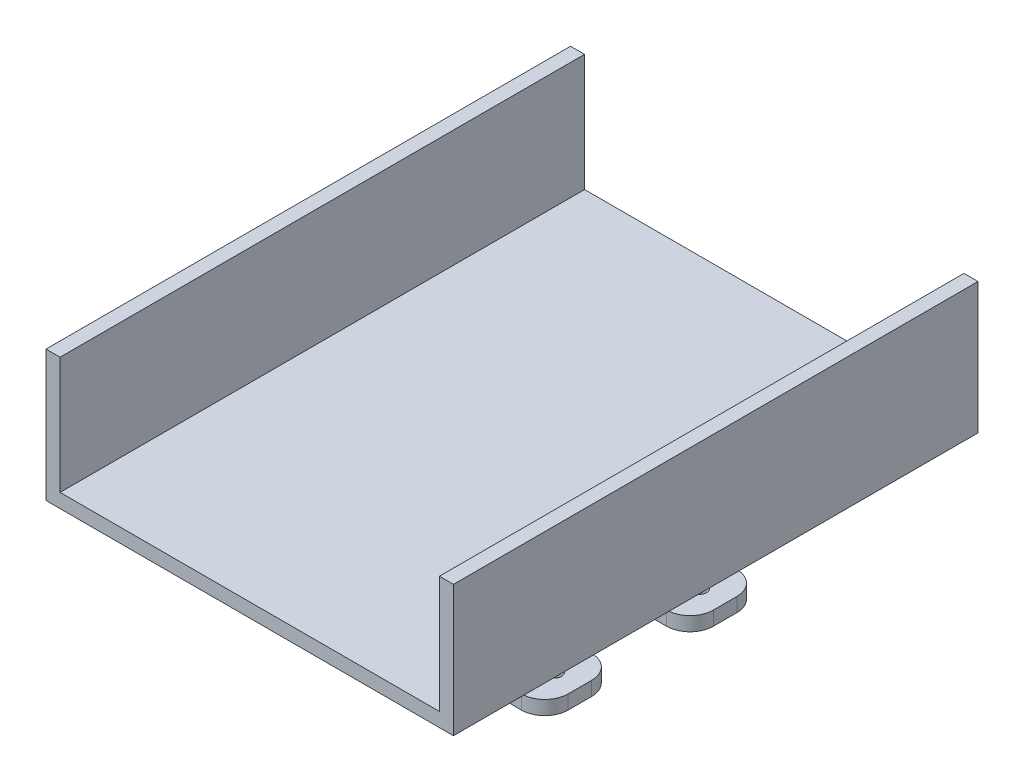
SolidWorks part; units mm, degrees
material "Du"
ref_plane "Front Plane" through (0, 0, 0) normal (0, 0, 1) x (1, 0, 0)
ref_plane "Top Plane" through (0, 0, 0) normal (0, 1, 0) x (1, 0, 0)
ref_plane "Right Plane" through (0, 0, 0) normal (1, 0, 0) x (0, 0, -1)
sketch "Sketch1" plane through (0, 0, 0) normal (0, 1, 0) x (1, 0, 0)
  line L1 (-43.5, -56) -> (43.5, -56)
  line L2 (-43.5, -56) -> (-43.5, 56)
  line L3 (-43.5, 56) -> (43.5, 56)
  line L4 (43.5, -56) -> (43.5, 56)
  line L5 (-43.5, -56) -> (43.5, 56) construction
  line L6 (-43.5, 56) -> (43.5, -56) construction
  point P0 (0, 0)
  dimension "D1" = 112
  dimension "D2" = 87
extrude "Boss-Extrude1" add sketch "Sketch1" along normal blind 3
sketch "Sketch2" plane through (0, 0, 0) normal (0, -1, 0) x (1, 0, 0)
  line L0 (0, 56) -> (0, -56) construction
  line L1 (-43.5, 56) -> (43.5, 56) construction
  line L2 (43.5, -56) -> (-43.5, -56) construction
  line L3 (-43.5, 0) -> (43.5, 0) construction
  line L4 (-43.5, -56) -> (-43.5, 56) construction
  line L5 (43.5, 56) -> (43.5, -56) construction
  line L6 (19, -14) -> (19, -17)
  line L7 (19, 14) -> (-19, 14)
  line L8 (19, 14) -> (19, 17)
  line L9 (19, 17) -> (-19, 17)
  line L10 (-19, 14) -> (-19, 17)
  line L11 (19, 14) -> (-19, 17) construction
  line L12 (19, 17) -> (-19, 14) construction
  line L13 (19, -14) -> (-19, -17) construction
  line L14 (19, -17) -> (-19, -14) construction
  line L15 (19, -14) -> (-19, -14)
  line L16 (-19, -14) -> (-19, -17)
  line L17 (19, -17) -> (-19, -17)
  point P12 (0, 15.5)
  point P21 (0, -15.5)
  dimension "D1" = 3
  dimension "D2" = 38
  dimension "D3" = 31
extrude "Boss-Extrude2" add sketch "Sketch2" along normal blind 18
sketch "Sketch8" plane through (0, -18, 0) normal (0, -1, 0) x (1, 0, 0)
  line L0 (19, -14) -> (-19, -14) construction
  line L1 (-19, -14) -> (-19, -17) construction
  line L2 (-19, -17) -> (19, -17) construction
  line L3 (19, -17) -> (19, -14) construction
  line L4 (-19, 17) -> (-19, 14) construction
  line L5 (-19, 14) -> (19, 14) construction
  line L6 (19, 14) -> (19, 17) construction
  line L7 (19, 17) -> (-19, 17) construction
  line L8 (19, -14) -> (-19, -14)
  line L9 (-19, -14) -> (-19, -17)
  line L10 (-19, -17) -> (19, -17)
  line L11 (19, -17) -> (19, -14)
  line L12 (-19, 17) -> (-19, 14)
  line L13 (-19, 14) -> (19, 14)
  line L14 (19, 14) -> (19, 17)
  line L15 (19, 17) -> (-19, 17)
  line L16 (0, 17) -> (0, -17) construction
  line L17 (-19, 15.5) -> (19, 15.5) construction
  line L18 (-19, -15.5) -> (19, -15.5) construction
  line L20 (30, 8) -> (-30, 8)
  line L21 (30, 8) -> (30, 23)
  line L22 (30, 23) -> (-30, 23)
  line L23 (-30, 8) -> (-30, 23)
  line L24 (30, 8) -> (-30, 23) construction
  line L25 (30, 23) -> (-30, 8) construction
  line L26 (30, -23) -> (-30, -23)
  line L27 (30, -23) -> (30, -8)
  line L28 (30, -8) -> (-30, -8)
  line L29 (-30, -23) -> (-30, -8)
  line L30 (30, -23) -> (-30, -8) construction
  line L31 (30, -8) -> (-30, -23) construction
  circle A0 centre (-24.5, 15.5) radius 1.575
  circle A1 centre (24.5, 15.5) radius 1.575
  circle A2 centre (-24.5, -15.5) radius 1.575
  circle A3 centre (24.5, -15.5) radius 1.575
  point P14 (0, 15.5)
  point P19 (0, -15.5)
  dimension "D5" = 3.15
  dimension "D7" = 3.15
  dimension "D1" = 15
  dimension "D2" = 60
  dimension "D3" = 15
  dimension "D4" = 60
  dimension "D6" = 5.5
  dimension "D8" = 5.5
extrude "Boss-Extrude5" add sketch "Sketch8" along normal blind 3 separate body
sketch "Sketch9" plane through (0, 0, 14) normal (0, 0, 1) x (1, 0, 0)
  line L4 (19, -18) -> (-19, -18)
  line L5 (-19, -18) -> (-19, -21)
  line L6 (-19, -21) -> (19, -21)
  line L7 (19, -21) -> (19, -18)
  line L8 (19, -18) -> (-19, -18)
  line L9 (-19, -18) -> (-19, -21)
  line L10 (-19, -21) -> (19, -21)
  line L11 (19, -21) -> (19, -18)
  dimension "D1" = 0
extrude "Boss-Extrude6" add sketch "Sketch9" along normal blind 3
sketch "Sketch10" plane through (0, 0, -14) normal (0, 0, -1) x (-1, 0, 0)
  line L4 (19, -18) -> (-19, -18)
  line L5 (-19, -18) -> (-19, -21)
  line L6 (-19, -21) -> (19, -21)
  line L7 (19, -21) -> (19, -18)
  line L8 (19, -18) -> (-19, -18)
  line L9 (-19, -18) -> (-19, -21)
  line L10 (-19, -21) -> (19, -21)
  line L11 (19, -21) -> (19, -18)
  dimension "D1" = 0
extrude "Boss-Extrude7" add sketch "Sketch10" along normal blind 3
fillet "Fillet2" radius 5 4 edges at (30, -19.5, -8) (-30, -19.5, -8) (30, -19.5, -23) (-30, -19.5, -23)
fillet "Fillet3" radius 5 4 edges at (-30, -19.5, 23) (30, -19.5, 23) (-30, -19.5, 8) (30, -19.5, 8)
fillet "Fillet4" radius 5 8 edges at (0, 0, 14) (0, 0, 17) (0, 0, -14) (0, 0, -17) (0, -18, 17) (0, -18, 14) (0, -18, -14) (0, -18, -17)
sketch "Sketch12" plane through (0, 3, 0) normal (0, 1, 0) x (1, 0, 0)
  line L0 (0, -56) -> (0, 56) construction
  line L1 (43.5, 56) -> (43.5, -56)
  line L2 (-43.5, 56) -> (-40.5, 56)
  line L3 (-43.5, 56) -> (-43.5, -56)
  line L4 (43.5, -56) -> (43.5, 56)
  line L5 (43.5, 56) -> (-43.5, 56)
  line L6 (-43.5, 56) -> (-43.5, -56)
  line L7 (-43.5, -56) -> (43.5, -56)
  line L8 (43.5, -56) -> (43.5, 56)
  line L9 (43.5, 56) -> (-43.5, 56)
  line L10 (-43.5, 56) -> (-43.5, -56)
  line L11 (-43.5, -56) -> (43.5, -56)
  line L12 (-43.5, -56) -> (-40.5, -56)
  line L13 (-40.5, 56) -> (-40.5, -56)
  line L14 (-42, -56) -> (-42, 56) construction
  line L15 (-43.5, 0) -> (-40.5, 0) construction
  line L16 (42, -56) -> (42, 56) construction
  line L17 (43.5, 0) -> (40.5, 0) construction
  line L18 (43.5, 56) -> (40.5, 56)
  line L19 (40.5, 56) -> (40.5, -56)
  line L20 (43.5, -56) -> (40.5, -56)
  point P82 (-42, 0)
  point P83 (42, 0)
  point P84 (43.5, 0)
  point P85 (42, 56)
  point P86 (40.5, 0)
  point P87 (42, -56)
  dimension "D2" = 3
  dimension "D3" = 112
  dimension "D1" = 0
extrude "Boss-Extrude8" add sketch "Sketch12" along normal blind 25 contours L3 L12 L13 L2 | L19 L20 L1 L18
